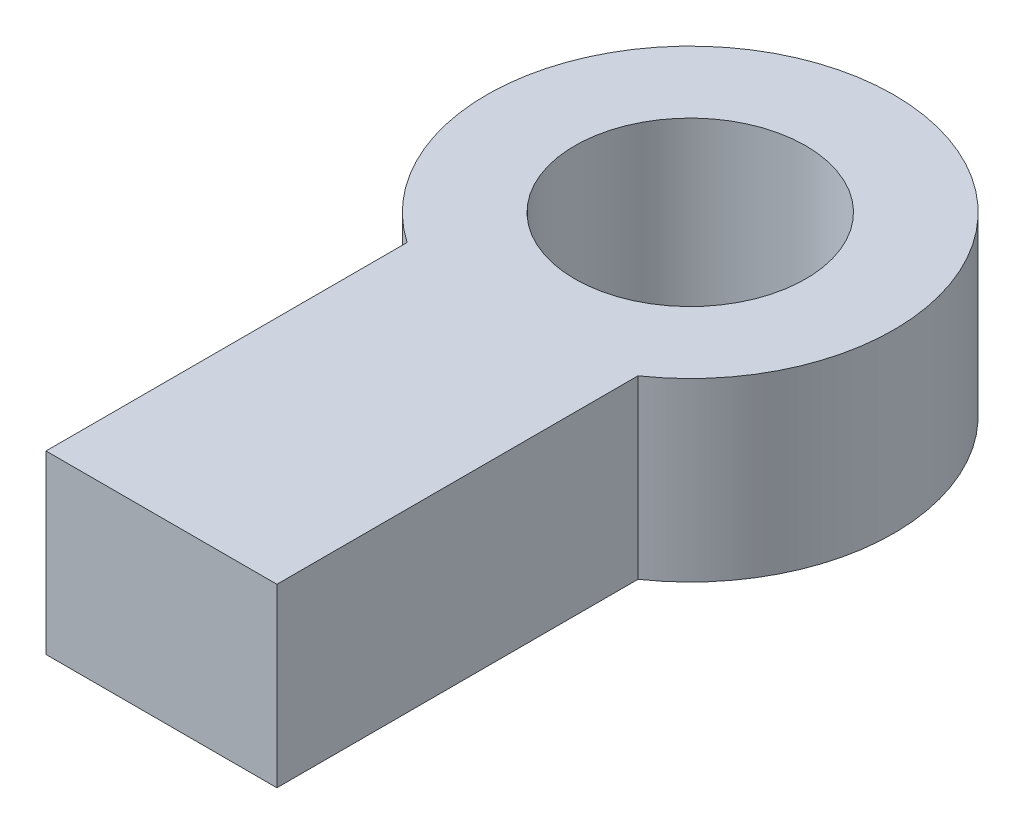
SolidWorks part; units mm, degrees
ref_plane "Front Plane" through (0, 0, 0) normal (1, 0, 0) x (0, 1, 0)
ref_plane "Top Plane" through (0, 0, 0) normal (0, 0, 1) x (0, 1, 0)
ref_plane "Right Plane" through (0, 0, 0) normal (0, 1, 0) x (-1, 0, 0)
sketch "Sketch1" plane through (0, 0, 0) normal (0, 1, 0) x (-1, 0, 0)
  circle A0 centre (0, 0) radius 3.3274
  circle A1 centre (0, 0) radius 5.8674
  dimension "D2" = 6.6548
  dimension "D1" = 2.54
extrude "Boss-Extrude1" add sketch "Sketch1" along normal blind 5.08
sketch "Sketch2" plane through (0, 0, 0) normal (0, -1, 0) x (1, 0, 0)
  line L0 (-3.3274, 0) -> (-3.3274, 15.24)
  line L1 (-3.3274, 15.24) -> (3.3274, 15.24)
  line L2 (3.3274, 15.24) -> (3.3274, 0)
  arc A0 (-3.3274, 0) -> (3.3274, 0) centre (0, 0) cw
  circle A1 centre (0, 0) radius 3.3274 construction
  dimension "D1" = 15.24
extrude "Boss-Extrude2" add sketch "Sketch2" against normal up to surface (5.08 mm away) up to face at (0, 5.08, 5.8674)
equation "\"shaft_d\"= 0.25in"
equation "\"clearance\"= 0.0120in"
equation "\"shrinkage\"= 1.03"
equation "\"shaft_diameter\" = ( \"shaft_d\" )"
equation "\"width\"= .4in"
equation "\"length\"= 5in"
equation "\"height\"= 0.5in"
equation "\"hole_diameter\" = ( ( \"clearance\" ) + \"shaft_d\" )"
equation "\"D2@Sketch1\"=\"hole_diameter\""
equation "\"D1@Boss-Extrude1\"= \"width\" * ( 1 / 2 )"
equation "\"D1@Sketch2\"= \"width\" * ( 6 / 4 )"
